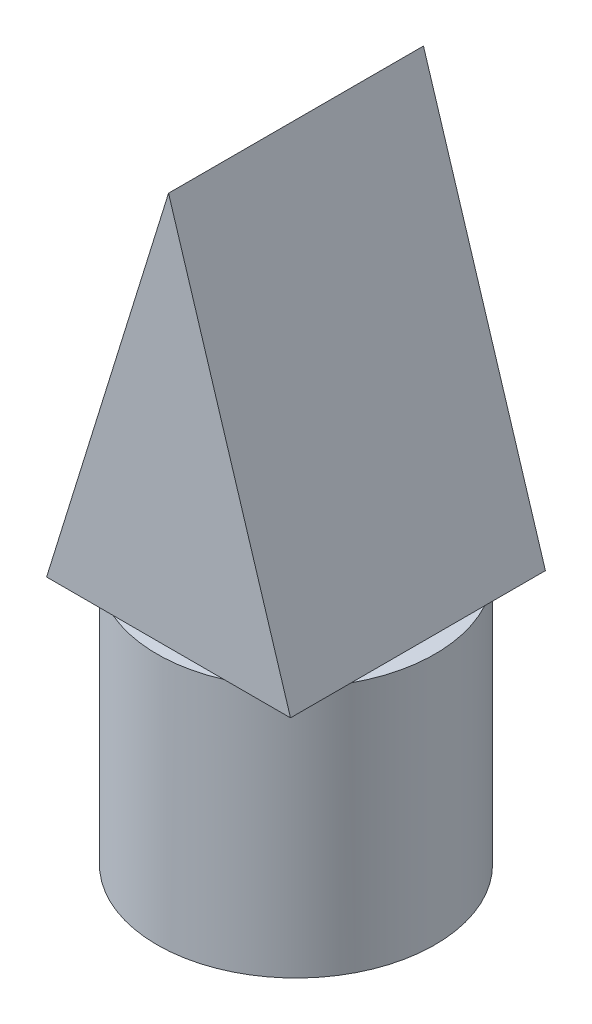
SolidWorks part; units mm, degrees
ref_plane "Front Plane" through (0, 0, 0) normal (0, 0, 1) x (1, 0, 0)
ref_plane "Top Plane" through (0, 0, 0) normal (0, 1, 0) x (1, 0, 0)
ref_plane "Right Plane" through (0, 0, 0) normal (1, 0, 0) x (0, 0, -1)
sketch "Sketch1" plane through (0, 0, 0) normal (0, 1, 0) x (1, 0, 0)
  circle A0 centre (0, 0) radius 5.3
  circle A1 centre (0, 0) radius 3.5
  dimension "D1" = 10.6
  dimension "D2" = 7
extrude "Boss-Extrude1" add sketch "Sketch1" along normal blind 9.6
sketch "Sketch2" plane through (0, 0, 0) normal (0, 0, 1) x (1, 0, 0)
  line L0 (-4.65, 9.6) -> (4.65, 9.6)
  line L1 (3.5, 9.6) -> (-3.5, 9.6) construction
  line L2 (-4.65, 9.6) -> (0, 24.6)
  line L3 (0, 24.6) -> (4.65, 9.6)
  point P2 (0, 9.6)
  dimension "D1" = 9.3
  dimension "D2" = 15
extrude "Boss-Extrude2" add sketch "Sketch2" along normal mid plane 9.72
